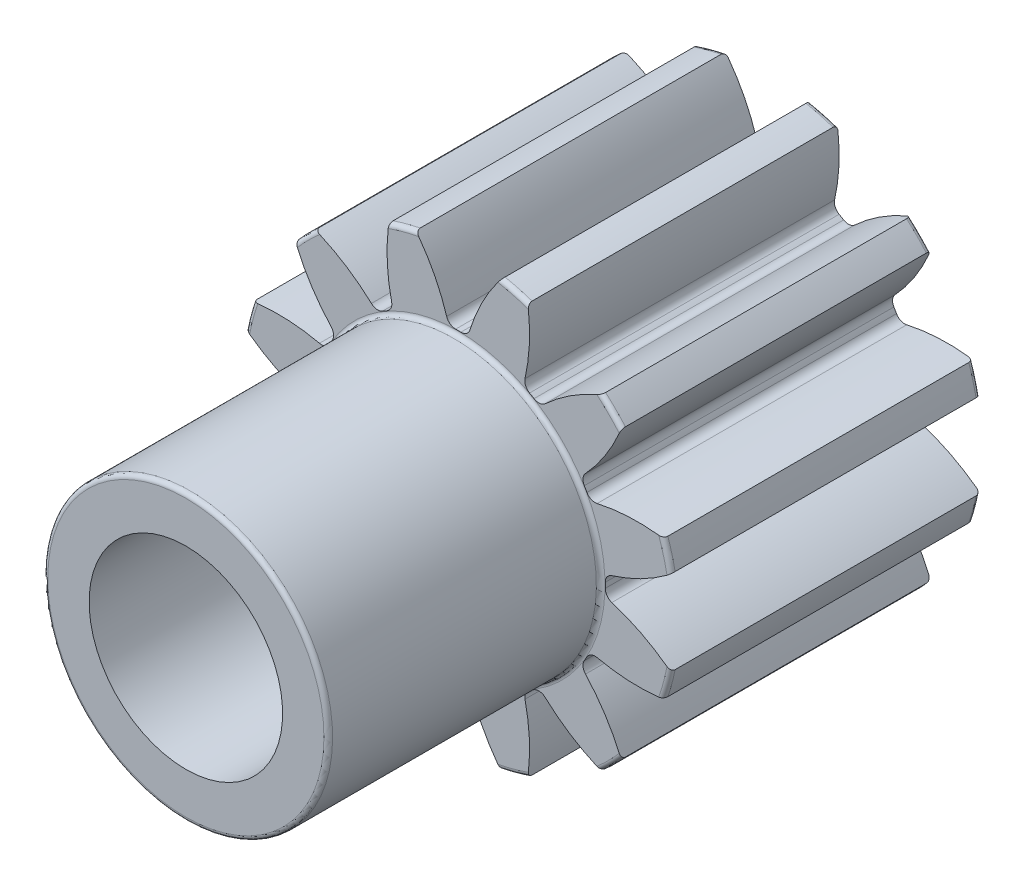
SolidWorks part; units mm, degrees
ref_plane "Front Plane" through (0, 0, 0) normal (0, 0, 1) x (1, 0, 0)
ref_plane "Top Plane" through (0, 0, 0) normal (0, 1, 0) x (1, 0, 0)
ref_plane "Right Plane" through (0, 0, 0) normal (1, 0, 0) x (0, 0, -1)
sketch "Sketch1" plane through (0, 0, 0) normal (0, 0, 1) x (1, 0, 0)
  line L0 (-152.4, 0) -> (152.4, 0) construction
  circle A0 centre (0, 0) radius 8.89 construction
  circle A1 centre (0, 0) radius 7.62 construction
  circle A2 centre (0, 0) radius 6.0325 construction
  circle A3 centre (0, 0) radius 5.842 construction
  circle A4 centre (0, 0) radius 3.9688 construction
  dimension "D1" = 2.8575
  dimension "OD" = 17.78
  dimension "Pitch Dia." = 15.24
  dimension "D2" = 1.27
  dimension "D3" = 2.8575
  dimension "Root Dia." = 12.065
  dimension "Hub Dia." = 11.684
  dimension "Shaft Dia." = 7.9375
  dimension "Number of Teeth" = 304.8
sketch "Sketch2" plane through (0, 0, 0) normal (1, 0, 0) x (0, 0, -1)
  line L0 (0, 0) -> (-12.7, 0) construction
  line L1 (-12.7, 0) -> (-23.876, 0) construction
  dimension "Overall Width" = 23.876
  dimension "Face Width" = 12.7
sketch "Sketch4" plane through (0, 0, 0) normal (1, 0, 0) x (0, 0, -1)
  line L0 (-23.876, 3.9688) -> (-23.876, 5.842)
  line L1 (-23.876, 5.842) -> (-12.7, 5.842)
  line L2 (-12.7, 5.842) -> (-12.7, 8.89)
  line L3 (-12.7, 8.89) -> (0, 8.89)
  line L4 (0, 8.89) -> (0, 3.9688)
  line L5 (-12.7, 5.842) -> (-12.7, 0) construction
  line L6 (0, 8.89) -> (0, -8.89) construction
  line L7 (-12.7, 5.842) -> (0, 5.842) construction
  line L12 (-23.876, 3.9688) -> (0, 3.9688)
revolve "Revolve1" add sketch "Sketch4" angle 360 about L1
fillet "Fillet2" radius 0.1778 4 edges at (0, 5.842, 23.876) (0, 5.842, 12.7) (0, 8.89, 12.7) (0, 8.89, 0)
sketch "Sketch7" plane through (0, 0, 12.7) normal (0, 0, 1) x (1, 0, 0)
  line L0 (0, 0) -> (0, 8.89) construction
  line L1 (0.9946, 7.5548) -> (1.6129, 8.7425) construction
  line L3 (2.3009, 8.5871) -> (1.9722, 7.3604) construction
  line L4 (1.9722, 7.3604) -> (1.5613, 5.8269) construction
  line L5 (0, 0) -> (1.5613, 5.8269) construction
  line L6 (0.9946, 7.5548) -> (0, 0) construction
  line L7 (0.9946, 7.5548) -> (1.1604, 8.8139) construction
  line L8 (0.9946, 7.5548) -> (0, 0) construction
  circle A0 centre (0, 0) radius 8.89 construction
  arc A1 (-0.1069, 6.0316) -> (0.1069, 6.0316) centre (0, 0) cw
  circle A2 centre (0, 0) radius 6.0325 construction
  arc A3 (-0.9946, 7.5548) -> (0.9946, 7.5548) centre (0, 0) cw construction
  circle A4 centre (0, 0) radius 7.62 construction
  arc A5 (2.8509, 8.4205) -> (1.7413, 8.7178) centre (0, 0) ccw construction
  arc A6 (0.9946, 7.5548) -> (2.916, 7.04) centre (0, 0) cw construction
  arc A7 (-1.7413, 8.7178) -> (1.7413, 8.7178) centre (0, 0) cw
  arc A8 (0.4774, 6.2994) -> (1.7413, 8.7178) centre (7.7536, 4.0363) cw
  arc A9 (-0.4774, 6.2994) -> (-1.7413, 8.7178) centre (-7.7536, 4.0363) ccw
  arc A10 (-0.1069, 6.0316) -> (-0.4774, 6.2994) centre (-0.1136, 6.4125) cw
  arc A11 (0.1069, 6.0316) -> (0.4774, 6.2994) centre (0.1136, 6.4125) ccw
  point P26 (-0.3962, 6.0195)
  point P29 (0.3962, 6.0195)
  dimension "D4" = 0.381
  dimension "D5" = 7.62
  dimension "D2" = 1.9949
  dimension "D1" = 3.9898
  dimension "D3" = 20
extrude "Cut-Extrude2" cut sketch "Sketch7" against normal through all
pattern_circular "CirPattern1" count 12 over 360 about axis through (0, 0, 0) along (0, 0, 1) of "Cut-Extrude2"
equation "\"D1@Sketch1\"=2.25*(\"Pitch Dia.@Sketch1\"/\"Number of Teeth@Sketch1\")"
equation "\"D1@CirPattern1\"=\"Number of Teeth@Sketch1\""
equation "\"D1@Fillet2\"=\"OD@Sketch1\"*.01"
equation "\"D1@Sketch7\"=3.14159*(\"Pitch Dia.@Sketch1\"/\"Number of Teeth@Sketch1\")"
equation "\"D2@Sketch7\"=\"D1@Sketch7\"/2"
equation "\"D4@Sketch7\"=\"D1@Sketch7\"*.0955"
equation "\"D5@Sketch7\"=\"Pitch Dia.@Sketch1\"/2"
